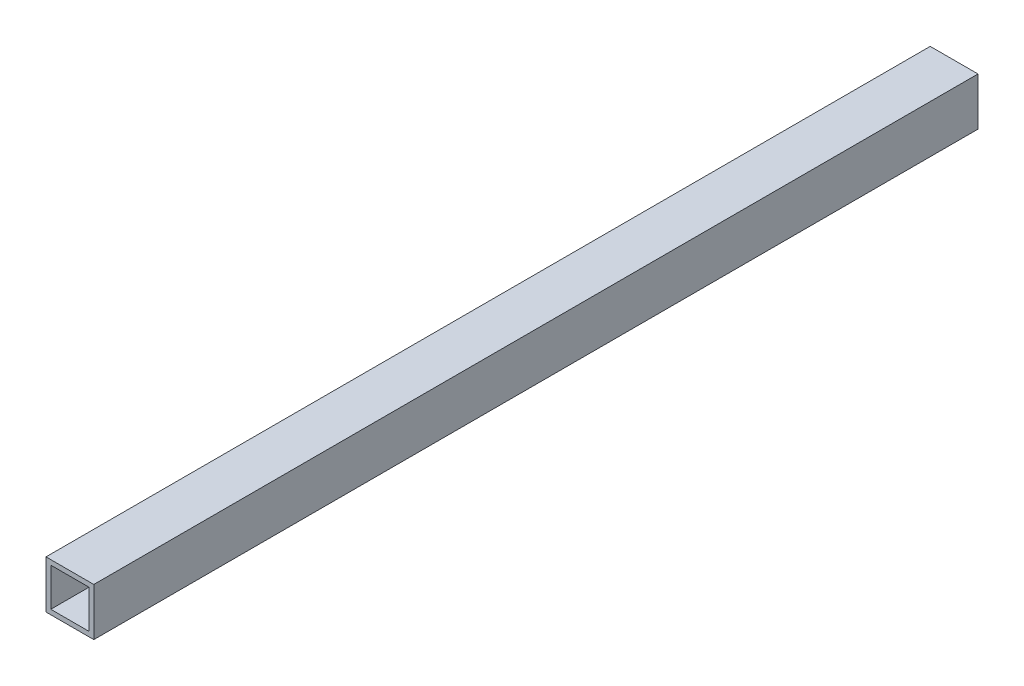
SolidWorks part; units mm, degrees
material "6063-O, Extruded Rod (SS)"
ref_plane "Front Plane" through (0, 0, 0) normal (0, 0, 1) x (1, 0, 0)
ref_plane "Top Plane" through (0, 0, 0) normal (0, 1, 0) x (1, 0, 0)
ref_plane "Right Plane" through (0, 0, 0) normal (1, 0, 0) x (0, 0, -1)
sketch "Sketch1" plane through (0, 0, 0) normal (0, 0, 1) x (1, 0, 0)
  line L0 (-10.16, 10.16) -> (10.16, 10.16)
  line L1 (-12.7, -12.7) -> (12.7, -12.7)
  line L2 (-12.7, -12.7) -> (-12.7, 12.7)
  line L3 (-12.7, 12.7) -> (12.7, 12.7)
  line L4 (12.7, -12.7) -> (12.7, 12.7)
  line L5 (-12.7, -12.7) -> (12.7, 12.7) construction
  line L6 (-12.7, 12.7) -> (12.7, -12.7) construction
  line L7 (10.16, -10.16) -> (10.16, 10.16)
  line L8 (-10.16, -10.16) -> (10.16, -10.16)
  line L9 (-10.16, -10.16) -> (-10.16, 10.16)
  point P0 (0, 0)
  dimension "D1" = 25.4
  dimension "D2" = 25.4
  dimension "D3" = 2.54
extrude "Boss-Extrude1" add sketch "Sketch1" along normal mid plane 469.9
